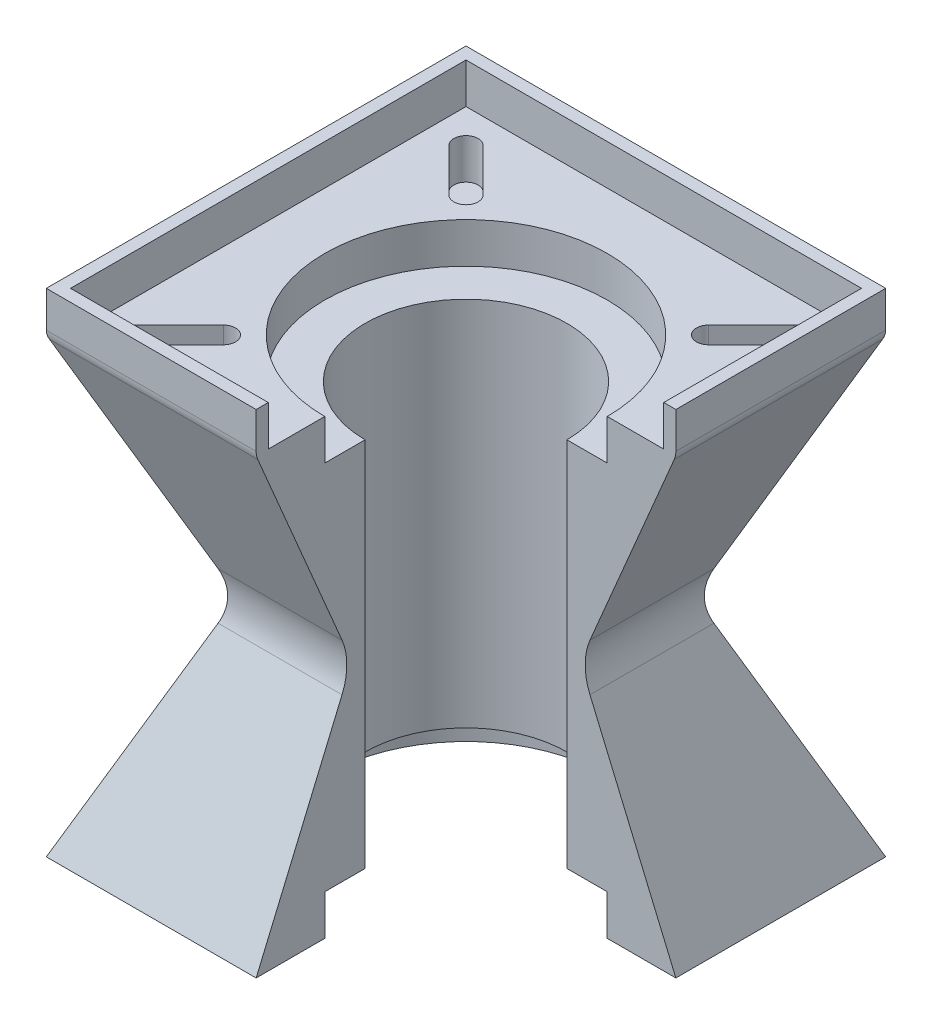
SolidWorks part; units mm, degrees
material "Acier inoxydable moulé"
ref_plane "Plan de face" through (0, 0, 0) normal (0, 0, 1) x (1, 0, 0)
ref_plane "Plan de dessus" through (0, 0, 0) normal (0, 1, 0) x (1, 0, 0)
ref_plane "Plan de droite" through (0, 0, 0) normal (1, 0, 0) x (0, 0, -1)
sketch "Esquisse1" plane through (0, 0, 0) normal (0, 1, 0) x (1, 0, 0)
  line L1 (-52, 52) -> (52, 52)
  line L2 (-52, 52) -> (-52, -52)
  line L3 (-52, -52) -> (52, -52)
  line L4 (52, 52) -> (52, -52)
  line L5 (-52, 52) -> (52, -52) construction
  line L6 (-52, -52) -> (52, 52) construction
  point P0 (0, 0)
  dimension "D1" = 104
  dimension "D2" = 104
extrude "Boss.-Extru.2" add sketch "Esquisse1" against normal blind 56 draft 23
mirror "Symétrie1" about plane through (0, -56, 0) normal (0, 1, 0) of "Boss.-Extru.2"
sketch "Esquisse2" plane through (0, 0, 0) normal (0, 1, 0) x (1, 0, 0)
  circle A0 centre (0, 0) radius 25
  dimension "D1" = 50
extrude "Enlèv. mat.-Extru.1" cut sketch "Esquisse2" against normal through all and the other way through all
fillet "Congé1" radius 15 4 edges at (0, -56, 28.2294) (28.2294, -56, 0) (0, -56, -28.2294) (-28.2294, -56, 0)
sketch "Esquisse3" plane through (0, 0, 0) normal (0, 1, 0) x (1, 0, 0)
  line L1 (52, -52) -> (0, -52)
  line L2 (52, -52) -> (52, 0)
  line L3 (52, 0) -> (0, 0)
  line L4 (0, -52) -> (0, 0)
extrude "Enlèv. mat.-Extru.2" cut sketch "Esquisse3" against normal through all
sketch "Esquisse4" plane through (0, 0, 0) normal (0, 1, 0) x (1, 0, 0)
  circle A0 centre (0, 0) radius 35
  dimension "D1" = 70
extrude "Enlèv. mat.-Extru.3" cut sketch "Esquisse4" against normal blind 10
ref_plane "Plan1" through (0, -56, 0) normal (0, 1, 0) x (1, 0, 0)
mirror "Symétrie2" about plane through (0, -56, 0) normal (0, 1, 0) of "Enlèv. mat.-Extru.3"
sketch "Esquisse7" plane through (0, 0, 0) normal (0, 1, 0) x (1, 0, 0)
  line L0 (-52, -52) -> (0, -52) construction
  line L1 (52, 0) -> (52, 52) construction
  line L2 (52, 52) -> (-52, 52) construction
  line L3 (-52, 52) -> (-52, -52) construction
  line L4 (-52, -52) -> (0, -52)
  line L5 (52, 0) -> (52, 52)
  line L6 (52, 52) -> (-52, 52)
  line L7 (-52, 52) -> (-52, -52)
  line L8 (49, 0) -> (49, 49)
  line L9 (49, 49) -> (-49, 49)
  line L10 (-49, 49) -> (-49, -49)
  line L11 (-49, -49) -> (0, -49)
  line L12 (52, 0) -> (49, 0)
  line L13 (0, -52) -> (0, -49)
  dimension "D1" = 3
extrude "Boss.-Extru.3" add sketch "Esquisse7" along normal blind 10
fillet "Congé2" radius 5 4 edges at (-52, 0, 0) (0, 0, -52) (52, 0, -26) (-26, 0, 52)
sketch "Esquisse8" plane through (0, 0, 0) normal (0, 1, 0) x (1, 0, 0)
  line L0 (0, 0) -> (-52, 52) construction
  line L1 (-40.6586, 40.6586) -> (-30.052, 30.052) construction
  line L2 (-38.5373, 42.78) -> (-27.9307, 32.1734)
  line L3 (-42.78, 38.5373) -> (-32.1734, 27.9307)
  line L4 (40.6586, 40.6586) -> (30.052, 30.052) construction
  line L5 (42.78, 38.5373) -> (32.1734, 27.9307)
  line L6 (38.5373, 42.78) -> (27.9307, 32.1734)
  line L7 (40.6586, -40.6586) -> (30.052, -30.052) construction
  line L8 (38.5373, -42.78) -> (27.9307, -32.1734)
  line L9 (42.78, -38.5373) -> (32.1734, -27.9307)
  line L10 (-40.6586, -40.6586) -> (-30.052, -30.052) construction
  line L11 (-42.78, -38.5373) -> (-32.1734, -27.9307)
  line L12 (-38.5373, -42.78) -> (-27.9307, -32.1734)
  arc A0 (-38.5373, 42.78) -> (-42.78, 38.5373) centre (-40.6586, 40.6586) ccw
  arc A1 (-32.1734, 27.9307) -> (-27.9307, 32.1734) centre (-30.052, 30.052) ccw
  circle A2 centre (0, 0) radius 50 construction
  arc A3 (42.78, 38.5373) -> (38.5373, 42.78) centre (40.6586, 40.6586) ccw
  arc A4 (27.9307, 32.1734) -> (32.1734, 27.9307) centre (30.052, 30.052) ccw
  arc A5 (38.5373, -42.78) -> (42.78, -38.5373) centre (40.6586, -40.6586) ccw
  arc A6 (32.1734, -27.9307) -> (27.9307, -32.1734) centre (30.052, -30.052) ccw
  arc A7 (-42.78, -38.5373) -> (-38.5373, -42.78) centre (-40.6586, -40.6586) ccw
  arc A8 (-27.9307, -32.1734) -> (-32.1734, -27.9307) centre (-30.052, -30.052) ccw
  point P6 (-35.3553, 35.3553)
  point P17 (35.3553, 35.3553)
  point P24 (35.3553, -35.3553)
  point P31 (-35.3553, -35.3553)
  point P36 (0, 0)
  dimension "D1" = 3
  dimension "D2" = 100
  dimension "D3" = 15
  dimension "D4" = 4
extrude "Enlèv. mat.-Extru.4" cut sketch "Esquisse8" against normal blind 10
equation "\"A\"= 112"
equation "\"B\"= 104"
equation "\"C\"= 23"
equation "\"D1@Esquisse1\"=\"B\""
equation "\"D2@Esquisse1\"=\"B\""
equation "\"D1@Boss.-Extru.2\"=\"A\" / 2"
equation "\"D3@Boss.-Extru.2\"=\"C\""
